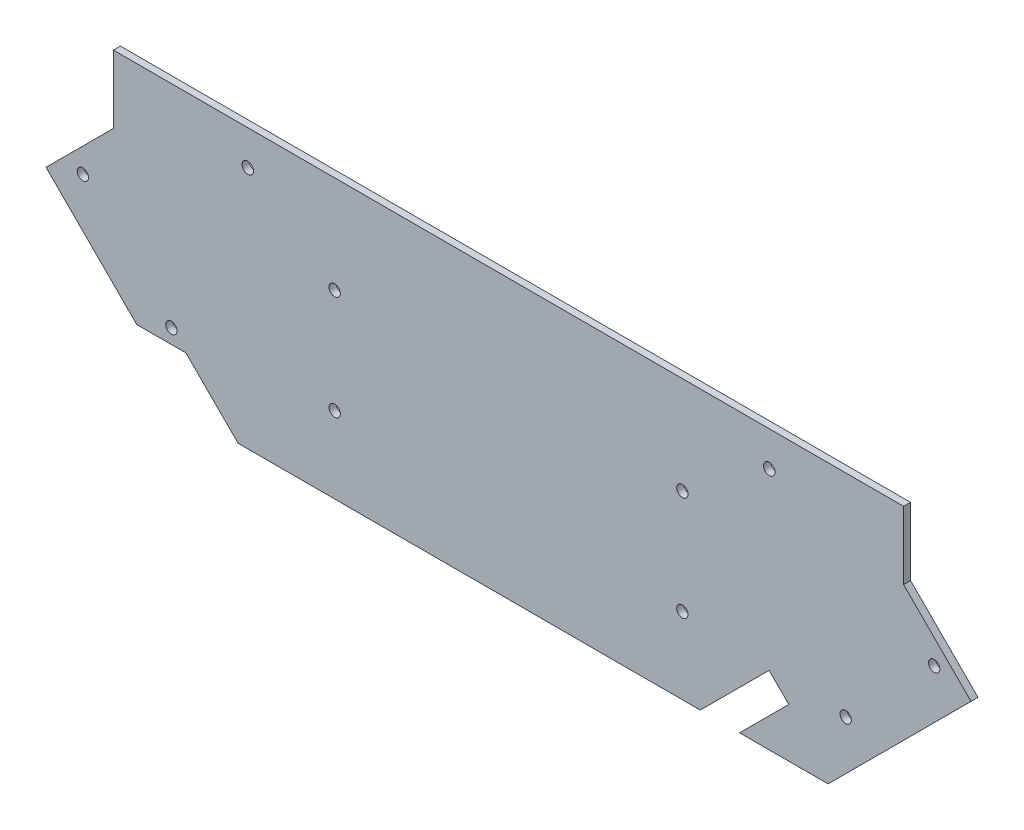
SolidWorks part; units mm, degrees
material "Thornel Mat VMA"
ref_plane "前视基准面" through (0, 0, 0) normal (0, 0, 1) x (1, 0, 0)
ref_plane "上视基准面" through (0, 0, 0) normal (0, 1, 0) x (1, 0, 0)
ref_plane "右视基准面" through (0, 0, 0) normal (1, 0, 0) x (0, 0, -1)
sketch "草图1" plane through (0, 0, 0) normal (0, 0, 1) x (1, 0, 0)
  line L1 (63.63, -40) -> (-63.63, -40)
  line L2 (63.63, -40) -> (63.63, 40)
  line L3 (63.63, 40) -> (-63.63, 40)
  line L4 (-63.63, -40) -> (-63.63, 40)
  line L5 (63.63, -40) -> (-63.63, 40) construction
  line L6 (63.63, 40) -> (-63.63, -40) construction
  line L7 (75, -15) -> (-75, -15) construction
  line L8 (75, -15) -> (75, 15) construction
  line L9 (75, 15) -> (-75, 15) construction
  line L10 (-75, -15) -> (-75, 15) construction
  line L11 (75, -15) -> (-75, 15) construction
  line L12 (75, 15) -> (-75, -15) construction
  line L13 (75, -24.5536) -> (-75, -24.5536) construction
  line L14 (75, -24.5536) -> (75, 5.4464) construction
  line L15 (75, 5.4464) -> (-75, 5.4464) construction
  line L16 (-75, -24.5536) -> (-75, 5.4464) construction
  line L17 (75, -24.5536) -> (-75, 5.4464) construction
  line L18 (75, 5.4464) -> (-75, -24.5536) construction
  circle A0 centre (-75, 15) radius 1.625 construction
  circle A1 centre (-75, -15) radius 1.625 construction
  circle A2 centre (75, 15) radius 1.625 construction
  circle A3 centre (75, -15) radius 1.625 construction
  point P0 (0, 0)
  point P6 (0, 0)
  point P15 (0, -9.5536)
  dimension "D5" = 3.25
  dimension "D1" = 127.26
  dimension "D2" = 80
  dimension "D3" = 30
  dimension "D4" = 150
  dimension "D6" = 150
  dimension "D7" = 30
extrude "凸台-拉伸1" add sketch "草图1" along normal blind 2
sketch "草图2" plane through (0, 0, 0) normal (0, 0, -1) x (-1, 0, 0)
  line L0 (63.63, 40) -> (143.63, 40)
  line L1 (143.63, 40) -> (63.63, -40) construction
  line L2 (-63.63, 40) -> (-143.63, 40)
  line L3 (-143.63, 40) -> (-63.63, -40) construction
  line L4 (-63.63, -40) -> (-63.63, 40)
  line L5 (143.63, 40) -> (157.7721, 25.8579)
  line L6 (157.7721, 25.8579) -> (91.9143, -40)
  line L7 (91.9143, -40) -> (63.63, -40)
  line L8 (-143.63, 40) -> (-157.7721, 25.8579)
  line L9 (-157.7721, 25.8579) -> (-91.9143, -40)
  line L10 (-91.9143, -40) -> (-63.63, -40)
  line M1 (63.63, -40) -> (63.63, 40)
  line M3 (-63.63, 40) -> (-63.63, -40)
  dimension "D1" = 20
extrude "凸台-拉伸2" add sketch "草图2" against normal up to surface (2 mm away) contours L1 L0 M1 | L2 L3 M3
sketch "草图3" plane through (0, 0, 2) normal (0, 0, 1) x (1, 0, 0)
  line L0 (143.63, 40) -> (-143.63, 40) construction
  line L1 (50, -18) -> (-50, -18) construction
  line L2 (50, -18) -> (50, 12) construction
  line L3 (50, 12) -> (-50, 12) construction
  line L4 (-50, -18) -> (-50, 12) construction
  line L5 (50, -18) -> (-50, 12) construction
  line L6 (50, 12) -> (-50, -18) construction
  line L7 (-150.7011, 32.9289) -> (-77.7721, -40) construction
  line L8 (-143.63, 40) -> (-157.7721, 25.8579) construction
  line L9 (-157.7721, 25.8579) -> (-91.9143, -40) construction
  line L10 (-91.9143, -40) -> (91.9143, -40) construction
  line L11 (-143.63, 40) -> (-157.7721, 25.8579) construction
  line L12 (0, -3) -> (0, -40) construction
  line L13 (-66.4584, -40) -> (-80.6006, -25.8579) construction
  line L14 (-80.6006, -25.8579) -> (-74.9437, -20.201) construction
  line L15 (-74.9437, -20.201) -> (-55.1447, -40) construction
  line L16 (-55.1447, -40) -> (-66.4584, -40) construction
  line L17 (80.6006, -25.8579) -> (74.9437, -20.201)
  line L18 (55.1447, -40) -> (66.4584, -40)
  line L19 (74.9437, -20.201) -> (55.1447, -40)
  line L20 (66.4584, -40) -> (80.6006, -25.8579)
  line L21 (-106.9143, -25) -> (-92.7721, -25)
  line L22 (-92.7721, -25) -> (-77.7721, -40)
  line L23 (-77.7721, -40) -> (-106.9143, -40)
  line L24 (-106.9143, -40) -> (-106.9143, -25)
  line L25 (-133.0234, 1.1091) -> (-113.63, 20.5025)
  line L27 (-113.63, 40) -> (-143.63, 40)
  line L28 (-143.63, 40) -> (-157.7721, 25.8579)
  line L29 (-157.7721, 25.8579) -> (-133.0234, 1.1091)
  line L30 (157.7721, 25.8579) -> (133.0234, 1.1091)
  line L31 (133.0234, 1.1091) -> (113.63, 20.5025)
  line L32 (143.63, 40) -> (157.7721, 25.8579)
  line L33 (113.63, 40) -> (143.63, 40)
  line L34 (113.63, 20.5025) -> (113.63, 40)
  line L35 (0, 30) -> (75, 30) construction
  line L36 (-113.63, 20.5025) -> (-113.63, 40)
  line L37 (0, 30) -> (-75, 30) construction
  line L38 (143.63, 40) -> (-143.63, 40) construction
  circle A0 centre (-50, 12) radius 1.625
  circle A1 centre (-50, -18) radius 1.625
  circle A2 centre (50, 12) radius 1.625
  circle A3 centre (50, -18) radius 1.625
  circle A4 centre (-122.4168, 4.6447) radius 1.625
  circle A5 centre (-96.961, -20.8112) radius 1.625
  circle A6 centre (96.961, -20.8112) radius 1.625
  circle A7 centre (122.4168, 4.6447) radius 1.625
  circle A8 centre (-75, 30) radius 1.65
  circle A9 centre (75, 30) radius 1.65
  point P0 (0, -3)
  dimension "D4" = 3.25
  dimension "D14" = 3.3
  dimension "D1" = 28
  dimension "D2" = 30
  dimension "D3" = 100
  dimension "D5" = 40
  dimension "D6" = 36
  dimension "D7" = 18
  dimension "D8" = 8
  dimension "D9" = 20
  dimension "D10" = 15
  dimension "D11" = 10
  dimension "D12" = 35
  dimension "D13" = 75
  dimension "D15" = 30
extrude "切除-拉伸1" cut sketch "草图3" against normal blind 32
